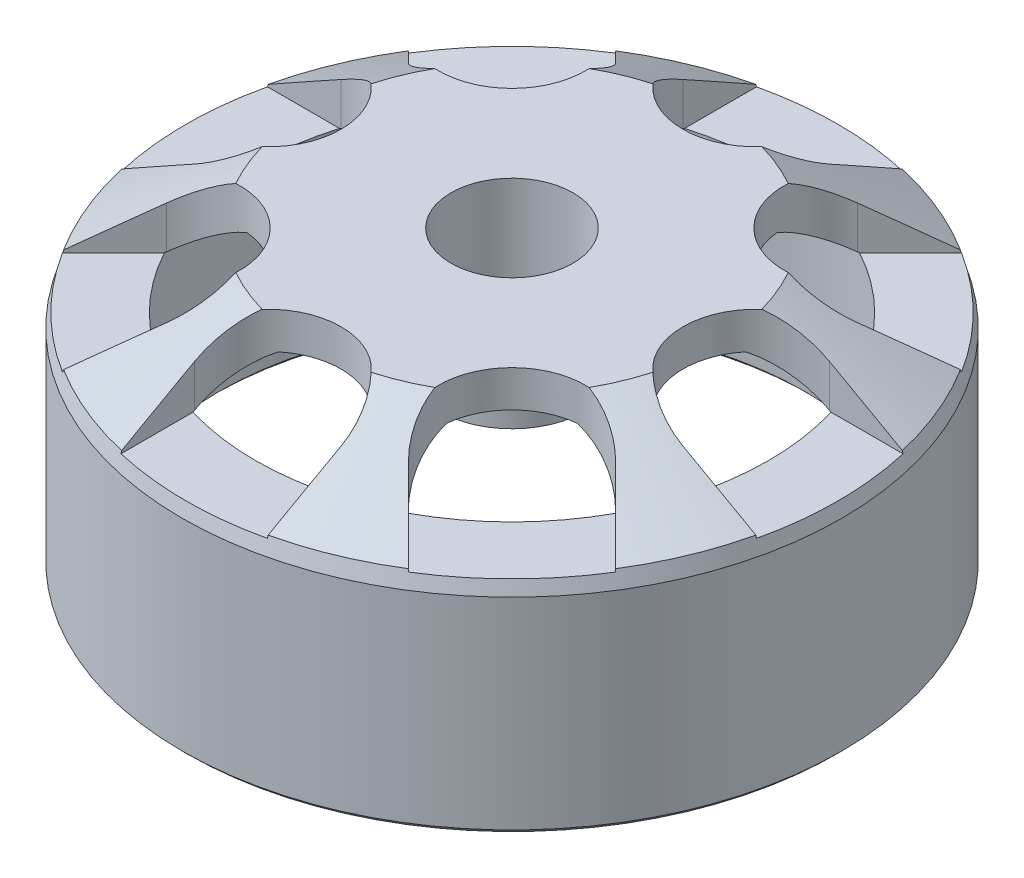
SolidWorks part; units mm, degrees
material "1060 Alloy"
ref_plane "Front Plane" through (0, 0, 0) normal (0, 0, 1) x (1, 0, 0)
ref_plane "Top Plane" through (0, 0, 0) normal (0, 1, 0) x (1, 0, 0)
ref_plane "Right Plane" through (0, 0, 0) normal (1, 0, 0) x (0, 0, -1)
sketch "Sketch1" plane through (0, 0, 0) normal (0, 0, 1) x (1, 0, 0)
  line L0 (0, 0) -> (0, 12.5) construction
  line L1 (-2.5, 7.5) -> (-2.5, 12.5)
  line L2 (-2.5, 12.5) -> (-8.3038, 12.5)
  line L3 (-8.3038, 12.5) -> (-13.5, 9.5)
  line L4 (-13.5, 9.5) -> (-13.5, 0.5)
  line L5 (-13.5, 0.5) -> (-12, 0.5)
  line L6 (-12, 0.5) -> (-12, 8.634)
  line L7 (-12, 8.634) -> (-7.9019, 11)
  line L8 (-7.9019, 11) -> (-3, 11)
  line L9 (-3, 11) -> (-3, 7.5)
  line L10 (-3, 7.5) -> (-2.5, 7.5)
  point P5 (-2.5, 10)
  point P14 (-5.451, 11)
  point P15 (0, 0)
  point P16 (0, 0)
  dimension "D1" = 13.5
  dimension "D2" = 2.5
  dimension "D3" = 3
  dimension "D4" = 12.5
  dimension "D5" = 120
  dimension "D6" = 12
  dimension "D7" = 1.5
  dimension "D8" = 1.5
  dimension "D9" = 1.5
  dimension "D10" = 3
  dimension "D11" = 5
revolve "Revolve1" add sketch "Sketch1" angle 360 about L0
chamfer "Chamfer1" distance 0.2 angle 45 3 edges at (0, 0.5, -12) (0, 0.5, -13.5) (0, 9.5, -13.5)
sketch "Sketch2" plane through (0, 12.5, 0) normal (0, 1, 0) x (1, 0, 0)
  line L0 (3, -10) -> (3, -15)
  line L1 (3, -15) -> (-3, -15)
  line L2 (-3, -15) -> (-3, -10)
  arc A0 (3, -10) -> (-3, -10) centre (0, -10) ccw
  dimension "D2" = 6
  dimension "D1" = 10
  dimension "D3" = 5
extrude "Cut-Extrude1" cut sketch "Sketch2" against normal blind 3
pattern_circular "CirPattern1" count 8 over 360 about axis through (0, 0, 0) along (0, 1, 0) of "Cut-Extrude1"
